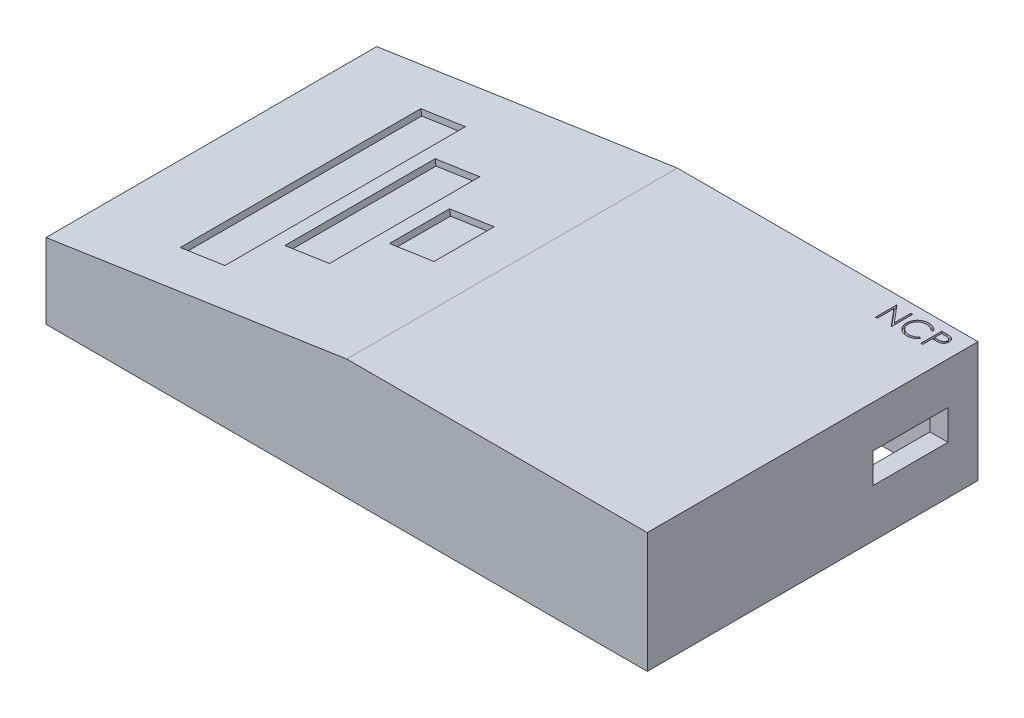
SolidWorks part; units mm, degrees
ref_plane "Front Plane" through (0, 0, 0) normal (0, 0, 1) x (1, 0, 0)
ref_plane "Top Plane" through (0, 0, 0) normal (0, 1, 0) x (1, 0, 0)
ref_plane "Right Plane" through (0, 0, 0) normal (1, 0, 0) x (0, 0, -1)
sketch "Sketch1" plane through (0, 0, 0) normal (0, 0, 1) x (1, 0, 0)
  line L0 (50, 20) -> (0, 12.5)
  line L1 (0, 0) -> (100, 0)
  line L2 (0, 0) -> (0, 20)
  line L3 (0, 20) -> (100, 20)
  line L4 (100, 0) -> (100, 20)
  dimension "D1" = 12.5
  dimension "D2" = 50
  dimension "D3" = 100
  dimension "D4" = 20
extrude "Boss-Extrude1" add sketch "Sketch1" along normal blind 55 contours L1 L4 L3 L0 L2
shell "Shell1" thickness 3
sketch "Sketch2" plane through (100, 0, 0) normal (1, 0, 0) x (0, 0, -1)
  line L1 (-17.5, 13) -> (-5, 13)
  line L2 (-17.5, 13) -> (-17.5, 8)
  line L3 (-17.5, 8) -> (-5, 8)
  line L4 (-5, 13) -> (-5, 8)
  line L5 (-55, 0) -> (0, 0) construction
  line L6 (0, 0) -> (0, 20) construction
  dimension "D1" = 5
  dimension "D2" = 12.5
  dimension "D3" = 8
  dimension "D4" = 5
extrude "Cut-Extrude1" cut sketch "Sketch2" against normal blind 5
sketch "Sketch3" plane through (-1.8337, 12.2249, 0) normal (-0.1483, 0.9889, 0) x (0.9889, 0.1483, 0)
  line L0 (52.4136, -55) -> (1.8543, -55) construction
  line L1 (34.3543, -15) -> (26.8543, -15)
  line L2 (34.3543, -15) -> (34.3543, -40)
  line L3 (34.3543, -40) -> (26.8543, -40)
  line L4 (26.8543, -15) -> (26.8543, -40)
  line L5 (24.3543, -7.5) -> (16.8543, -7.5)
  line L6 (24.3543, -7.5) -> (24.3543, -47.5)
  line L7 (24.3543, -47.5) -> (16.8543, -47.5)
  line L8 (16.8543, -7.5) -> (16.8543, -47.5)
  line L9 (44.3543, -22.5) -> (36.8543, -22.5)
  line L10 (44.3543, -22.5) -> (44.3543, -32.5)
  line L11 (44.3543, -32.5) -> (36.8543, -32.5)
  line L12 (36.8543, -22.5) -> (36.8543, -32.5)
  line L13 (1.8543, -55) -> (1.8543, 0) construction
  dimension "D1" = 40
  dimension "D2" = 7.5
  dimension "D3" = 7.5
  dimension "D4" = 15
  dimension "D5" = 2.5
  dimension "D6" = 7.5
  dimension "D7" = 25
  dimension "D8" = 7.5
  dimension "D9" = 2.5
  dimension "D10" = 7.5
  dimension "D11" = 7.5
  dimension "D12" = 10
extrude "Cut-Extrude2" cut sketch "Sketch3" against normal blind 1
sketch "Sketch4" plane through (0, 20, 0) normal (0, 1, 0) x (1, 0, 0)
  line L0 (50, 0) -> (100, 0) construction
  line L1 (100, -55) -> (100, 0) construction
  text T0 "NCP"
  dimension "D1" = 5
  dimension "D2" = 12.5
extrude "Cut-Extrude3" cut sketch "Sketch4" against normal blind 0.5
sketch "Sketch5" plane through (0, 17, 0) normal (0, -1, 0) x (1, 0, 0)
  line L0 (50.2237, 52) -> (97, 52) construction
  line L1 (97, 52) -> (97, 3) construction
  circle A0 centre (93.75, 27.75) radius 2
  circle A1 centre (67.25, 46.25) radius 2
  dimension "D5" = 4
  dimension "D6" = 4
  dimension "D1" = 24.25
  dimension "D2" = 3.25
  dimension "D3" = 5.75
  dimension "D4" = 29.75
extrude "Boss-Extrude2" add sketch "Sketch5" along normal blind 7.5
sketch "Sketch6" plane through (0, 9.5, 0) normal (0, -1, 0) x (1, 0, 0)
  circle A0 centre (67.25, 46.25) radius 1.125
  circle A1 centre (93.75, 27.75) radius 1.125
  dimension "D1" = 2.25
  dimension "D2" = 2.25
extrude "Boss-Extrude3" add sketch "Sketch6" along normal blind 5
sketch "Sketch7" plane through (0, 17, 0) normal (0, -1, 0) x (1, 0, 0)
  line L1 (97, 3) -> (74, 3)
  line L2 (97, 3) -> (97, 19.5)
  line L3 (97, 19.5) -> (74, 19.5)
  line L4 (74, 3) -> (74, 19.5)
  dimension "D1" = 16.5
  dimension "D2" = 23
extrude "Boss-Extrude4" add sketch "Sketch7" along normal offset from surface (2.25 mm away) 1.75 up to face at (98.5, 13, 11.25)
sketch "Sketch8" plane through (0, 14.75, 0) normal (0, -1, 0) x (1, 0, 0)
  line L0 (74, 11.25) -> (97, 11.25) construction
  line L1 (74, 19.5) -> (80.25, 19.5)
  line L2 (74, 19.5) -> (74, 14.85)
  line L3 (74, 14.85) -> (80.25, 14.85)
  line L4 (80.25, 19.5) -> (80.25, 14.85)
  line L5 (74, 3) -> (74, 19.5) construction
  line L6 (97, 19.5) -> (97, 3) construction
  line L7 (80.25, 3) -> (80.25, 7.65)
  line L8 (75, 14.85) -> (74, 14.85)
  line L9 (75, 14.85) -> (75, 13)
  line L10 (75, 13) -> (74, 13)
  line L11 (74, 14.85) -> (74, 13)
  line L12 (74, 7.65) -> (80.25, 7.65)
  line L13 (74, 3) -> (80.25, 3)
  line L14 (74, 7.65) -> (74, 9.5)
  line L15 (75, 9.5) -> (74, 9.5)
  line L16 (75, 7.65) -> (75, 9.5)
  line L17 (75, 7.65) -> (74, 7.65)
  line L18 (74, 3) -> (74, 7.65)
  line M1 (97, 19.5) -> (74, 19.5)
  line M2 (74, 19.5) -> (74, 3)
  line M3 (74, 3) -> (97, 3)
  dimension "D1" = 3.6
  dimension "D2" = 16.75
  dimension "D3" = 1.75
  dimension "D4" = 5.25
extrude "Boss-Extrude5" add sketch "Sketch8" along normal blind 1 contours L12 L7 M2 M3 | L10 L9 L3 M2 | L4 L3 M1 M2 | L17 L16 L15 L14
